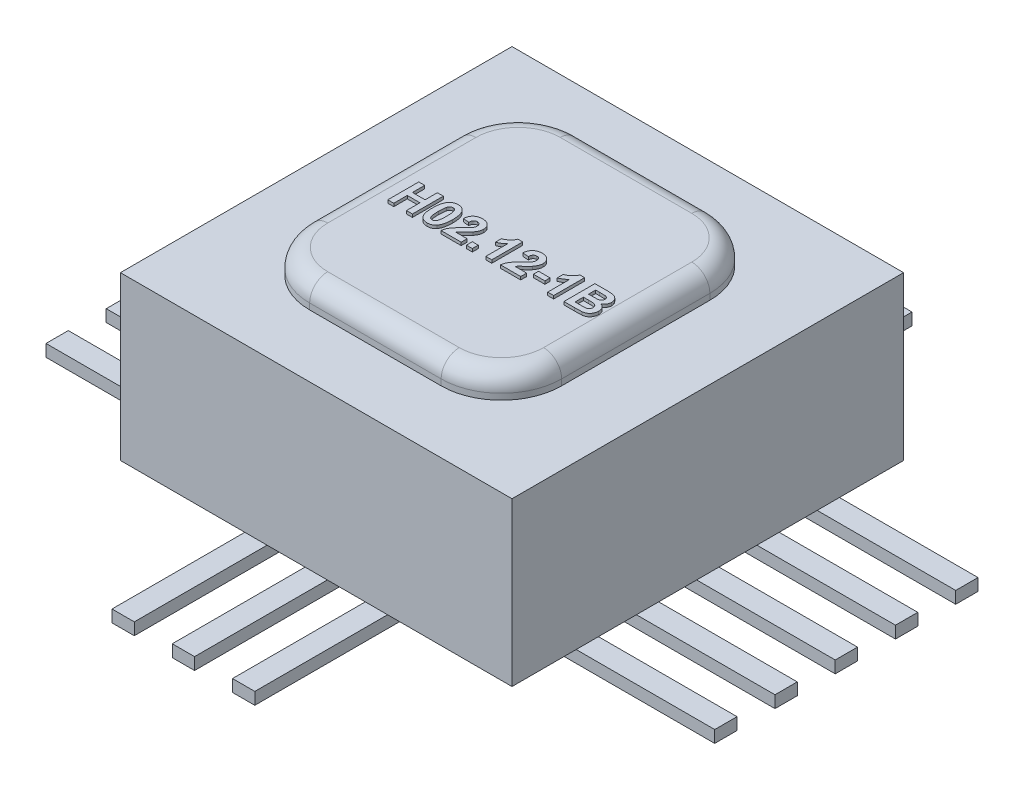
SolidWorks part; units mm, degrees
ref_plane "Спереди" through (0, 0, 0) normal (0, 0, 1) x (1, 0, 0)
ref_plane "Сверху" through (0, 0, 0) normal (0, 1, 0) x (1, 0, 0)
ref_plane "Справа" through (0, 0, 0) normal (1, 0, 0) x (0, 0, -1)
sketch "Эскиз1" plane through (0, 0, 0) normal (0, 1, 0) x (1, 0, 0)
  line L1 (-7.497, 4.9136) -> (-0.997, 4.9136)
  line L2 (-7.497, 4.9136) -> (-7.497, -1.5864)
  line L3 (-7.497, -1.5864) -> (-0.997, -1.5864)
  line L4 (-0.997, 4.9136) -> (-0.997, -1.5864)
  dimension "D1" = 6.5
  dimension "D2" = 6.5
extrude "Бобышка-Вытянуть1" add sketch "Эскиз1" along normal blind 2.7
sketch "Эскиз2" plane through (0, 2.7, 0) normal (0, 1, 0) x (1, 0, 0)
  line L4 (-5.3899, 3.9082) -> (-3.2075, 3.9082)
  line L6 (-2.2075, 2.9082) -> (-2.2075, 0.4482)
  line L7 (-3.2075, -0.5518) -> (-5.3899, -0.5518)
  line L8 (-6.3899, 0.4482) -> (-6.3899, 2.9082)
  arc A0 (-2.2075, 2.9082) -> (-3.2075, 3.9082) centre (-3.2075, 2.9082) ccw
  arc A1 (-2.2075, 0.4482) -> (-3.2075, -0.5518) centre (-3.2075, 0.4482) cw
  arc A2 (-5.3899, -0.5518) -> (-6.3899, 0.4482) centre (-5.3899, 0.4482) cw
  arc A3 (-6.3899, 2.9082) -> (-5.3899, 3.9082) centre (-5.3899, 2.9082) cw
  point P19 (-2.2075, 3.9082)
  point P22 (-2.2075, -0.5518)
  point P25 (-6.3899, -0.5518)
  point P28 (-6.3899, 3.9082)
  dimension "D1" = 1
extrude "Бобышка-Вытянуть2" add sketch "Эскиз2" along normal blind 0.4
sketch "Эскиз3" plane through (0, 3.1, 0) normal (0, 1, 0) x (1, 0, 0)
  text T0 "<b>H02.12-1B</b>" font "Arial" height in points 2
extrude "Бобышка-Вытянуть3" add sketch "Эскиз3" along normal blind 0.05
sketch "Эскиз4" plane through (0, 0, 0) normal (0, -1, 0) x (1, 0, 0)
  line L0 (-7.497, 1.5864) -> (-0.997, -4.9136) construction
  line L1 (-0.997, 1.5864) -> (-7.497, -4.9136) construction
  line L2 (-1.497, -1.8486) -> (-1.497, -1.4786)
  line L3 (-4.247, -1.6636) -> (-4.247, -4.318) construction
  line L5 (-4.247, -4.318) -> (-4.062, -4.318)
  line L6 (-4.062, -4.318) -> (-4.062, -7.118)
  line L7 (-4.247, -4.318) -> (-4.432, -4.318)
  line L8 (-4.062, -7.118) -> (-4.432, -7.118)
  line L9 (-1.497, -1.8486) -> (1.303, -1.8486)
  line L10 (1.303, -1.8486) -> (1.303, -1.4786)
  line L11 (1.303, -1.4786) -> (-1.497, -1.4786)
  line L12 (-4.432, -7.118) -> (-4.432, -4.318)
  line L13 (-3.247, -4.318) -> (-3.062, -4.318)
  line L14 (-3.062, -4.318) -> (-3.062, -7.118)
  line L15 (-3.247, -4.318) -> (-3.432, -4.318)
  line L16 (-3.062, -7.118) -> (-3.432, -7.118)
  line L17 (-3.432, -7.118) -> (-3.432, -4.318)
  line L18 (-1.497, -2.8486) -> (1.303, -2.8486)
  line L19 (1.303, -2.4786) -> (-1.497, -2.4786)
  line L20 (1.303, -2.8486) -> (1.303, -2.4786)
  line L21 (-1.497, -2.8486) -> (-1.497, -2.4786)
  line L22 (-1.497, -3.8486) -> (1.303, -3.8486)
  line L23 (1.303, -3.4786) -> (-1.497, -3.4786)
  line L24 (1.303, -3.8486) -> (1.303, -3.4786)
  line L25 (-1.497, -3.8486) -> (-1.497, -3.4786)
  line L26 (-5.247, -4.318) -> (-5.062, -4.318)
  line L27 (-5.062, -4.318) -> (-5.062, -7.118)
  line L28 (-5.247, -4.318) -> (-5.432, -4.318)
  line L29 (-5.062, -7.118) -> (-5.432, -7.118)
  line L30 (-5.432, -7.118) -> (-5.432, -4.318)
  line L31 (-9.797, 0.5214) -> (-6.997, 0.5214)
  line L32 (-9.797, 0.1514) -> (-9.797, 0.5214)
  line L33 (-6.997, 0.1514) -> (-9.797, 0.1514)
  line L34 (-1.497, -0.8486) -> (-1.497, -0.4786)
  line L35 (-1.497, -0.8486) -> (1.303, -0.8486)
  line L36 (1.303, -0.8486) -> (1.303, -0.4786)
  line L37 (1.303, -0.4786) -> (-1.497, -0.4786)
  line L38 (-1.497, 0.1514) -> (-1.497, 0.5214)
  line L39 (-1.497, 0.1514) -> (1.303, 0.1514)
  line L40 (1.303, 0.1514) -> (1.303, 0.5214)
  line L41 (1.303, 0.5214) -> (-1.497, 0.5214)
  line L42 (-6.997, 0.1514) -> (-6.997, 0.5214)
  line L43 (-9.797, -0.4786) -> (-6.997, -0.4786)
  line L44 (-9.797, -0.8486) -> (-9.797, -0.4786)
  line L45 (-6.997, -0.8486) -> (-9.797, -0.8486)
  line L46 (-6.997, -0.8486) -> (-6.997, -0.4786)
  line L47 (-6.997, -3.8486) -> (-6.997, -3.4786)
  line L48 (-9.797, -3.8486) -> (-9.797, -3.4786)
  line L49 (-9.797, -3.4786) -> (-6.997, -3.4786)
  line L50 (-6.997, -3.8486) -> (-9.797, -3.8486)
  line L51 (-6.997, -2.8486) -> (-6.997, -2.4786)
  line L52 (-9.797, -2.8486) -> (-9.797, -2.4786)
  line L53 (-9.797, -2.4786) -> (-6.997, -2.4786)
  line L54 (-6.997, -2.8486) -> (-9.797, -2.8486)
  line L55 (-9.797, -1.4786) -> (-6.997, -1.4786)
  line L56 (-9.797, -1.8486) -> (-9.797, -1.4786)
  line L57 (-6.997, -1.8486) -> (-9.797, -1.8486)
  line L58 (-6.997, -1.8486) -> (-6.997, -1.4786)
  line L59 (-4.247, -1.6636) -> (-0.997, -1.6636) construction
  line L60 (-0.997, 1.5864) -> (-0.997, -4.9136) construction
  line L61 (-5.432, 3.7907) -> (-5.432, 0.9907)
  line L62 (-5.062, 3.7907) -> (-5.432, 3.7907)
  line L63 (-5.247, 0.9907) -> (-5.432, 0.9907)
  line L64 (-5.062, 0.9907) -> (-5.062, 3.7907)
  line L65 (-9.297, -1.8486) -> (-6.497, -1.8486) [skipped]
  line L66 (-6.497, -1.4786) -> (-9.297, -1.4786) [skipped]
  line L67 (-5.247, 0.9907) -> (-5.062, 0.9907)
  line L68 (-9.297, -1.8486) -> (-9.297, -1.4786) [skipped]
  line L69 (-9.297, -1.8486) -> (-9.297, -1.4786) [skipped]
  line L70 (-9.297, -2.8486) -> (-9.297, -2.4786) [skipped]
  line L71 (-9.297, -3.8486) -> (-9.297, -3.4786) [skipped]
  line L72 (-9.297, -0.8486) -> (-9.297, -0.4786) [skipped]
  line L73 (-9.297, 0.1514) -> (-9.297, 0.5214) [skipped]
  line L74 (-9.297, -3.8486) -> (-6.497, -3.8486) [skipped]
  line L75 (-6.497, -3.4786) -> (-9.297, -3.4786) [skipped]
  line L76 (-3.432, 3.7907) -> (-3.432, 0.9907)
  line L77 (-9.297, -2.8486) -> (-6.497, -2.8486) [skipped]
  line L78 (-9.297, -1.8486) -> (-6.497, -1.8486) [skipped]
  line L79 (-3.062, 3.7907) -> (-3.432, 3.7907)
  line L80 (-6.497, -1.4786) -> (-9.297, -1.4786) [skipped]
  line L81 (-6.497, -2.4786) -> (-9.297, -2.4786) [skipped]
  line L82 (-3.247, 0.9907) -> (-3.432, 0.9907)
  line L83 (-9.297, -0.8486) -> (-6.497, -0.8486) [skipped]
  line L84 (-3.062, 0.9907) -> (-3.062, 3.7907)
  line L85 (-6.497, -0.4786) -> (-9.297, -0.4786) [skipped]
  line L86 (-9.297, 0.1514) -> (-6.497, 0.1514) [skipped]
  line L87 (-3.247, 0.9907) -> (-3.062, 0.9907)
  line L88 (-6.497, 0.5214) -> (-9.297, 0.5214) [skipped]
  line L90 (-4.432, 3.7907) -> (-4.432, 0.9907)
  line L91 (-4.062, 3.7907) -> (-4.432, 3.7907)
  line L92 (-4.247, 0.9907) -> (-4.432, 0.9907)
  line L93 (-4.062, 0.9907) -> (-4.062, 3.7907)
  line L94 (-4.247, 0.9907) -> (-4.062, 0.9907)
  dimension "D1" = 2
  dimension "D2" = 2
  dimension "D4" = 3
  dimension "D6" = 2
  dimension "D5" = 2
  dimension "D3" = 3
extrude "Бобышка-Вытянуть4" add sketch "Эскиз4" along normal blind 0.2
fillet "Скругление1" radius 0.3 8 edges at (-2.5004, 3.1, -3.6153) (-2.2075, 3.1, -1.6782) (-2.5004, 3.1, 0.2589) (-4.2987, 3.1, 0.5518) (-6.097, 3.1, 0.2589) (-6.3899, 3.1, -1.6782) (-6.097, 3.1, -3.6153) (-4.2987, 3.1, -3.9082)
